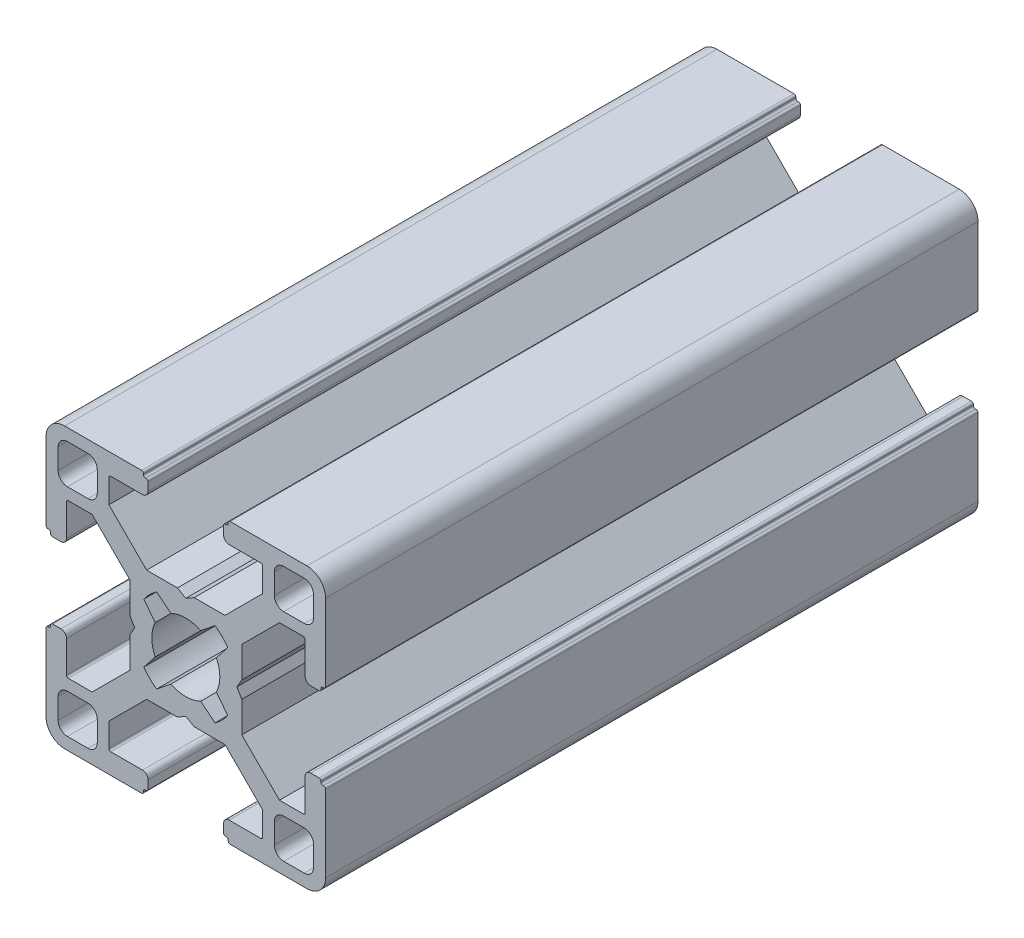
SolidWorks part; units mm, degrees
material "6061 Alloy"
ref_plane "Front" through (0, 0, 0) normal (0, 0, 1) x (1, 0, 0)
ref_plane "Top" through (0, 0, 0) normal (0, 1, 0) x (1, 0, 0)
ref_plane "Right" through (0, 0, 0) normal (1, 0, 0) x (0, 0, -1)
sketch "Sketch1" plane through (0, 0, 0) normal (0, 0, 1) x (1, 0, 0)
  line L0 (13.7, 12.7) -> (13.7, 10.5)
  line L1 (10.5, 9.5) -> (12.7, 9.5)
  line L2 (9.5, 12.7) -> (9.5, 10.5)
  line L3 (10.5, 13.7) -> (12.7, 13.7)
  line L4 (3.1359, 4.5184) -> (1.6001, 3.2806)
  line L5 (3.2806, 1.6001) -> (4.5053, 3.1547)
  line L6 (6.0045, 0.9) -> (5.4849, 0)
  line L7 (6.0045, 4.2045) -> (6.0045, 0.9)
  line L8 (0, -5.4849) -> (0.9, -6)
  line L9 (0.9, -6) -> (4.2045, -6)
  line L10 (4.2045, -6) -> (8.25, -10.05)
  line L11 (8.25, -10.05) -> (8.25, -12.6)
  line L12 (4.65, -12.8) -> (8.05, -12.8)
  line L13 (4.05, -14.3) -> (4.05, -13.4)
  line L14 (4.25, -14.5) -> (4.35, -14.5)
  line L15 (4.55, -14.8) -> (4.55, -14.7)
  line L16 (4.75, -15) -> (13, -15)
  line L17 (15, -13) -> (15, -4.75)
  line L18 (14.7, -4.55) -> (14.8, -4.55)
  line L19 (14.5, -4.35) -> (14.5, -4.25)
  line L20 (13.4, -4.05) -> (14.3, -4.05)
  line L21 (12.8, -8.05) -> (12.8, -4.65)
  line L22 (12.6, -8.25) -> (10.05, -8.25)
  line L23 (10.05, -8.25) -> (6.0045, -4.2045)
  line L24 (6.0045, -4.2045) -> (6.0045, -0.9)
  line L25 (6.0045, -0.9) -> (5.4849, 0)
  line L26 (10.05, 8.25) -> (6.0045, 4.2045)
  line L27 (12.6, 8.25) -> (10.05, 8.25)
  line L28 (12.8, 8.05) -> (12.8, 4.65)
  line L29 (13.4, 4.05) -> (14.3, 4.05)
  line L30 (14.5, 4.35) -> (14.5, 4.25)
  line L31 (14.7, 4.55) -> (14.8, 4.55)
  line L32 (15, 13) -> (15, 4.75)
  line L33 (4.75, 15) -> (13, 15)
  line L34 (4.55, 14.8) -> (4.55, 14.7)
  line L35 (4.25, 14.5) -> (4.35, 14.5)
  line L36 (4.05, 14.3) -> (4.05, 13.4)
  line L37 (4.65, 12.8) -> (8.05, 12.8)
  line L38 (8.25, 10.05) -> (8.25, 12.6)
  line L39 (4.2045, 6) -> (8.25, 10.05)
  line L40 (0.9, 6) -> (4.2045, 6)
  line L41 (0, 5.4849) -> (0.9, 6)
  line L42 (-13.7, -12.7) -> (-13.7, -10.5)
  line L43 (-10.5, -9.5) -> (-12.7, -9.5)
  line L44 (-9.5, -12.7) -> (-9.5, -10.5)
  line L45 (-10.5, -13.7) -> (-12.7, -13.7)
  line L46 (-3.1359, -4.5184) -> (-1.6001, -3.2806)
  line L47 (-3.2806, -1.6001) -> (-4.5053, -3.1547)
  line L48 (0, 5.4849) -> (-0.9, 6)
  line L49 (-0.9, 6) -> (-4.2045, 6)
  line L50 (-4.2045, 6) -> (-8.25, 10.05)
  line L51 (-8.25, 10.05) -> (-8.25, 12.6)
  line L52 (-4.65, 12.8) -> (-8.05, 12.8)
  line L53 (-4.05, 14.3) -> (-4.05, 13.4)
  line L54 (-4.25, 14.5) -> (-4.35, 14.5)
  line L55 (-4.55, 14.8) -> (-4.55, 14.7)
  line L56 (-4.75, 15) -> (-13, 15)
  line L57 (-15, 13) -> (-15, 4.75)
  line L58 (-14.7, 4.55) -> (-14.8, 4.55)
  line L59 (-14.5, 4.35) -> (-14.5, 4.25)
  line L60 (-13.4, 4.05) -> (-14.3, 4.05)
  line L61 (-12.8, 8.05) -> (-12.8, 4.65)
  line L62 (-12.6, 8.25) -> (-10.05, 8.25)
  line L63 (-10.05, 8.25) -> (-6.0045, 4.2045)
  line L64 (-6.0045, -0.9) -> (-5.4849, 0)
  line L65 (-6.0045, -4.2045) -> (-6.0045, -0.9)
  line L66 (-10.05, -8.25) -> (-6.0045, -4.2045)
  line L67 (-12.6, -8.25) -> (-10.05, -8.25)
  line L68 (-12.8, -8.05) -> (-12.8, -4.65)
  line L69 (-13.4, -4.05) -> (-14.3, -4.05)
  line L70 (-14.5, -4.35) -> (-14.5, -4.25)
  line L71 (-14.7, -4.55) -> (-14.8, -4.55)
  line L72 (-15, -13) -> (-15, -4.75)
  line L73 (-4.75, -15) -> (-13, -15)
  line L74 (-4.55, -14.8) -> (-4.55, -14.7)
  line L75 (-4.25, -14.5) -> (-4.35, -14.5)
  line L76 (-4.05, -14.3) -> (-4.05, -13.4)
  line L77 (3.2806, -1.6001) -> (4.5053, -3.1547)
  line L78 (3.1359, -4.5184) -> (1.6001, -3.2806)
  line L79 (-4.65, -12.8) -> (-8.05, -12.8)
  line L80 (-8.25, -10.05) -> (-8.25, -12.6)
  line L81 (-4.2045, -6) -> (-8.25, -10.05)
  line L82 (-0.9, -6) -> (-4.2045, -6)
  line L83 (0, -5.4849) -> (-0.9, -6)
  line L84 (10.5, -13.7) -> (12.7, -13.7)
  line L85 (9.5, -12.7) -> (9.5, -10.5)
  line L86 (10.5, -9.5) -> (12.7, -9.5)
  line L87 (13.7, -12.7) -> (13.7, -10.5)
  line L88 (-6.0045, 4.2045) -> (-6.0045, 0.9)
  line L89 (-6.0045, 0.9) -> (-5.4849, 0)
  line L90 (-3.2806, 1.6001) -> (-4.5053, 3.1547)
  line L91 (-3.1359, 4.5184) -> (-1.6001, 3.2806)
  line L92 (-10.5, 13.7) -> (-12.7, 13.7)
  line L93 (-9.5, 12.7) -> (-9.5, 10.5)
  line L94 (-10.5, 9.5) -> (-12.7, 9.5)
  line L95 (-13.7, 12.7) -> (-13.7, 10.5)
  line L96 (-23.4857, 0) -> (20.9308, 0) construction
  line L97 (0, 17.9563) -> (0, -17.361) construction
  arc A0 (13.7, 12.7) -> (12.7, 13.7) centre (12.7, 12.7) ccw
  arc A1 (12.7, 9.5) -> (13.7, 10.5) centre (12.7, 10.5) ccw
  arc A2 (9.5, 10.5) -> (10.5, 9.5) centre (10.5, 10.5) ccw
  arc A3 (10.5, 13.7) -> (9.5, 12.7) centre (10.5, 12.7) ccw
  arc A4 (1.6001, 3.2806) -> (-1.6001, 3.2806) centre (0, 0) ccw
  arc A5 (8.25, -12.6) -> (8.05, -12.8) centre (8.05, -12.6) cw
  arc A6 (4.65, -12.8) -> (4.05, -13.4) centre (4.65, -13.4) ccw
  arc A7 (4.05, -14.3) -> (4.25, -14.5) centre (4.25, -14.3) ccw
  arc A8 (4.35, -14.5) -> (4.55, -14.7) centre (4.35, -14.7) cw
  arc A9 (4.55, -14.8) -> (4.75, -15) centre (4.75, -14.8) ccw
  arc A10 (13, -15) -> (15, -13) centre (13, -13) ccw
  arc A11 (15, -4.75) -> (14.8, -4.55) centre (14.8, -4.75) ccw
  arc A12 (14.7, -4.55) -> (14.5, -4.35) centre (14.7, -4.35) cw
  arc A13 (14.5, -4.25) -> (14.3, -4.05) centre (14.3, -4.25) ccw
  arc A14 (13.4, -4.05) -> (12.8, -4.65) centre (13.4, -4.65) ccw
  arc A15 (12.8, -8.05) -> (12.6, -8.25) centre (12.6, -8.05) cw
  arc A16 (4.5053, 3.1547) -> (3.1359, 4.5184) centre (0, 0) ccw
  arc A17 (12.8, 8.05) -> (12.6, 8.25) centre (12.6, 8.05) ccw
  arc A18 (13.4, 4.05) -> (12.8, 4.65) centre (13.4, 4.65) cw
  arc A19 (14.5, 4.25) -> (14.3, 4.05) centre (14.3, 4.25) cw
  arc A20 (14.7, 4.55) -> (14.5, 4.35) centre (14.7, 4.35) ccw
  arc A21 (15, 4.75) -> (14.8, 4.55) centre (14.8, 4.75) cw
  arc A22 (13, 15) -> (15, 13) centre (13, 13) cw
  arc A23 (4.55, 14.8) -> (4.75, 15) centre (4.75, 14.8) cw
  arc A24 (4.35, 14.5) -> (4.55, 14.7) centre (4.35, 14.7) ccw
  arc A25 (4.05, 14.3) -> (4.25, 14.5) centre (4.25, 14.3) cw
  arc A26 (4.65, 12.8) -> (4.05, 13.4) centre (4.65, 13.4) cw
  arc A27 (8.25, 12.6) -> (8.05, 12.8) centre (8.05, 12.6) ccw
  arc A28 (-13.7, -12.7) -> (-12.7, -13.7) centre (-12.7, -12.7) ccw
  arc A29 (-12.7, -9.5) -> (-13.7, -10.5) centre (-12.7, -10.5) ccw
  arc A30 (-9.5, -10.5) -> (-10.5, -9.5) centre (-10.5, -10.5) ccw
  arc A31 (-10.5, -13.7) -> (-9.5, -12.7) centre (-10.5, -12.7) ccw
  arc A32 (-4.5053, -3.1547) -> (-3.1359, -4.5184) centre (0, 0) ccw
  arc A33 (-3.2806, 1.6001) -> (-3.2806, -1.6001) centre (0, 0) ccw
  arc A34 (-8.25, 12.6) -> (-8.05, 12.8) centre (-8.05, 12.6) cw
  arc A35 (-4.65, 12.8) -> (-4.05, 13.4) centre (-4.65, 13.4) ccw
  arc A36 (-4.05, 14.3) -> (-4.25, 14.5) centre (-4.25, 14.3) ccw
  arc A37 (-4.35, 14.5) -> (-4.55, 14.7) centre (-4.35, 14.7) cw
  arc A38 (-4.55, 14.8) -> (-4.75, 15) centre (-4.75, 14.8) ccw
  arc A39 (-13, 15) -> (-15, 13) centre (-13, 13) ccw
  arc A40 (-15, 4.75) -> (-14.8, 4.55) centre (-14.8, 4.75) ccw
  arc A41 (-14.7, 4.55) -> (-14.5, 4.35) centre (-14.7, 4.35) cw
  arc A42 (-14.5, 4.25) -> (-14.3, 4.05) centre (-14.3, 4.25) ccw
  arc A43 (-13.4, 4.05) -> (-12.8, 4.65) centre (-13.4, 4.65) ccw
  arc A44 (-12.8, 8.05) -> (-12.6, 8.25) centre (-12.6, 8.05) cw
  arc A45 (-4.5053, 3.1547) -> (-3.1359, 4.5184) centre (0, 0) cw
  arc A46 (-12.8, -8.05) -> (-12.6, -8.25) centre (-12.6, -8.05) ccw
  arc A47 (-13.4, -4.05) -> (-12.8, -4.65) centre (-13.4, -4.65) cw
  arc A48 (-14.5, -4.25) -> (-14.3, -4.05) centre (-14.3, -4.25) cw
  arc A49 (3.2806, 1.6001) -> (3.2806, -1.6001) centre (0, 0) cw
  arc A50 (4.5053, -3.1547) -> (3.1359, -4.5184) centre (0, 0) cw
  arc A51 (1.6001, -3.2806) -> (-1.6001, -3.2806) centre (0, 0) cw
  arc A52 (-14.7, -4.55) -> (-14.5, -4.35) centre (-14.7, -4.35) ccw
  arc A53 (-15, -4.75) -> (-14.8, -4.55) centre (-14.8, -4.75) cw
  arc A54 (-13, -15) -> (-15, -13) centre (-13, -13) cw
  arc A55 (-4.55, -14.8) -> (-4.75, -15) centre (-4.75, -14.8) cw
  arc A56 (10.5, -13.7) -> (9.5, -12.7) centre (10.5, -12.7) cw
  arc A57 (9.5, -10.5) -> (10.5, -9.5) centre (10.5, -10.5) cw
  arc A58 (12.7, -9.5) -> (13.7, -10.5) centre (12.7, -10.5) cw
  arc A59 (13.7, -12.7) -> (12.7, -13.7) centre (12.7, -12.7) cw
  arc A60 (-4.35, -14.5) -> (-4.55, -14.7) centre (-4.35, -14.7) ccw
  arc A61 (-4.05, -14.3) -> (-4.25, -14.5) centre (-4.25, -14.3) cw
  arc A62 (-4.65, -12.8) -> (-4.05, -13.4) centre (-4.65, -13.4) cw
  arc A63 (-8.25, -12.6) -> (-8.05, -12.8) centre (-8.05, -12.6) ccw
  arc A64 (-10.5, 13.7) -> (-9.5, 12.7) centre (-10.5, 12.7) cw
  arc A65 (-9.5, 10.5) -> (-10.5, 9.5) centre (-10.5, 10.5) cw
  arc A66 (-12.7, 9.5) -> (-13.7, 10.5) centre (-12.7, 10.5) cw
  arc A67 (-13.7, 12.7) -> (-12.7, 13.7) centre (-12.7, 12.7) cw
  point P81 (15, 15)
  point P82 (0, 15)
  point P203 (0, -15)
  point P204 (15, -15)
  point P206 (0, 0)
  point P207 (15, 0)
  point P219 (-15, 0)
  point P220 (-15, -15)
  point P221 (-15, 15)
extrude "Base-Extrude" add sketch "Sketch1" against normal blind 70
sketch "草图2" plane through (15, 0, 0) normal (1, 0, 0) x (0, 0, -1)
  line L0 (0, 15) -> (30, -15)
  line L1 (70, -15) -> (0, -15) construction
  line L2 (0, 4.75) -> (0, 13) construction
  line L3 (0, 15) -> (0, -15)
  line L4 (0, -15) -> (30, -15)
  line L5 (-13.0087, 11.9543) -> (-11.263, 12.8943)
  dimension "D1" = 45
